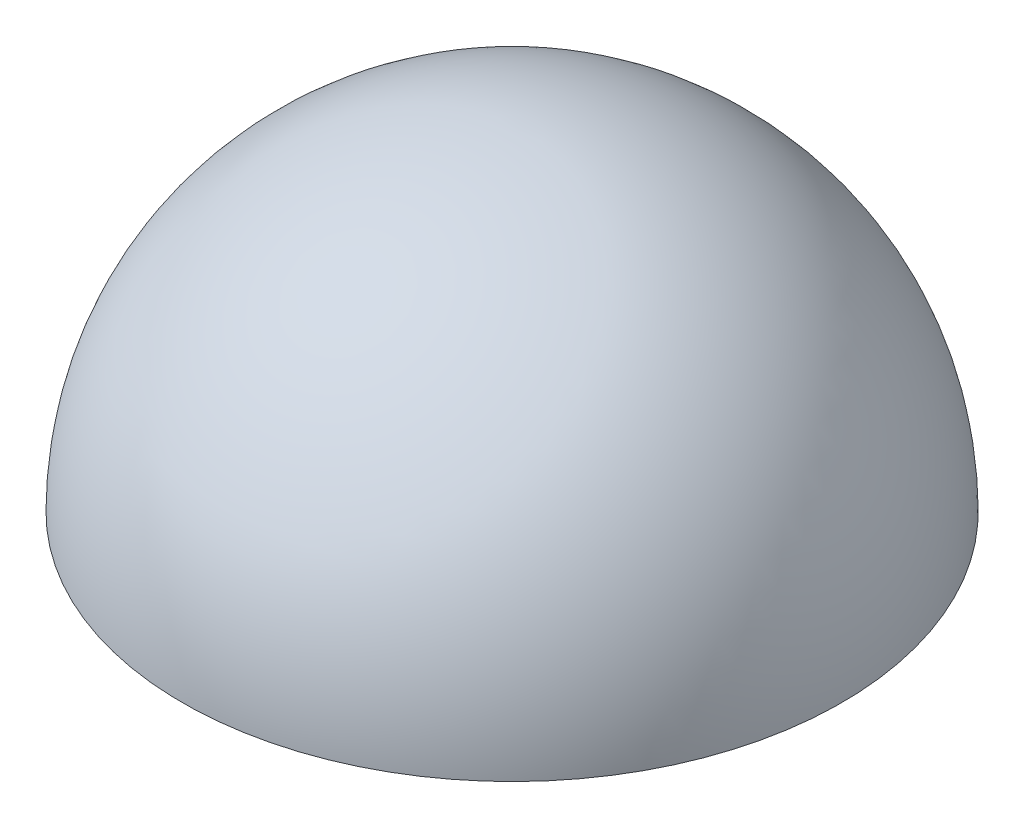
SolidWorks part; units mm, degrees
ref_plane "Front Plane" through (0, 0, 0) normal (0, 0, 1) x (1, 0, 0)
ref_plane "Top Plane" through (0, 0, 0) normal (0, 1, 0) x (1, 0, 0)
ref_plane "Right Plane" through (0, 0, 0) normal (1, 0, 0) x (0, 0, -1)
sketch "Sketch1" plane through (0, 0, 0) normal (0, 1, 0) x (1, 0, 0)
  line L0 (-10, 0) -> (10, 0)
  arc A0 (10, 0) -> (-10, 0) centre (0, 0) ccw
  dimension "D1" = 20
revolve "Revolve1" add sketch "Sketch1" angle 180 about L0
sketch "Sketch2" plane through (0, 0, 0) normal (0, -1, 0) x (1, 0, 0)
  circle A0 centre (0, 0) radius 4
  dimension "D1" = 8
extrude "Cut-Extrude1" cut sketch "Sketch2" against normal blind 5
